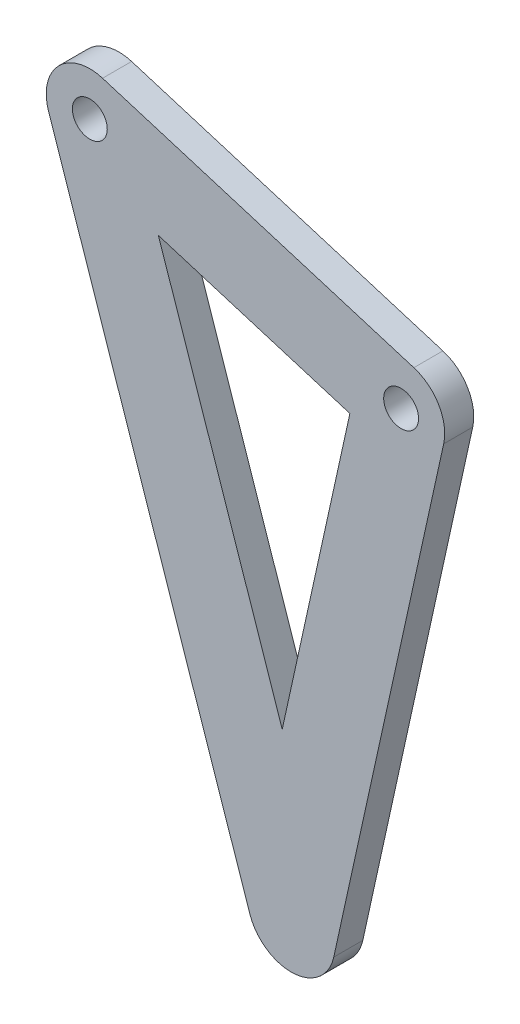
SolidWorks part; units mm, degrees
ref_plane "Plan de face" through (0, 0, 0) normal (0, 0, 1) x (1, 0, 0)
ref_plane "Plan de dessus" through (0, 0, 0) normal (0, 1, 0) x (1, 0, 0)
ref_plane "Plan de droite" through (0, 0, 0) normal (1, 0, 0) x (0, 0, -1)
sketch "Esquisse1" plane through (0, 0, 0) normal (0, 0, 1) x (1, 0, 0)
  line L0 (-104.5852, -42.1267) -> (-51.0249, -58.4761) construction
  line L1 (-102.3955, -34.9534) -> (-48.8353, -51.3029)
  line L2 (-106.7748, -49.2999) -> (-53.2146, -65.6494)
  line L3 (-51.0249, -58.4761) -> (-69.9405, -144.4191) construction
  line L4 (-43.7003, -60.0882) -> (-62.6158, -146.0313)
  line L5 (-58.3496, -56.864) -> (-77.2652, -142.807)
  line L6 (-69.9405, -144.4191) -> (-104.5852, -42.1267) construction
  line L7 (-77.0441, -146.825) -> (-111.6888, -44.5326)
  line L8 (-62.8368, -142.0133) -> (-97.4815, -39.7208)
  line L9 (-92.7916, -53.5684) -> (-71.4762, -116.5046)
  line L10 (-71.4762, -116.5046) -> (-59.8382, -63.6275)
  line L11 (-59.8382, -63.6275) -> (-92.7916, -53.5684)
  line L12 (-43.7003, -60.0882) -> (-62.6158, -146.0313)
  line L13 (-102.3955, -34.9534) -> (-48.8353, -51.3029)
  line L14 (-111.6888, -44.5326) -> (-77.0441, -146.825)
  arc A0 (-102.3955, -34.9534) -> (-106.7748, -49.2999) centre (-104.5852, -42.1267) ccw
  arc A1 (-53.2146, -65.6494) -> (-48.8353, -51.3029) centre (-51.0249, -58.4761) ccw
  arc A2 (-43.7003, -60.0882) -> (-58.3496, -56.864) centre (-51.0249, -58.4761) ccw
  arc A3 (-77.2652, -142.807) -> (-62.6158, -146.0313) centre (-69.9405, -144.4191) ccw
  arc A4 (-77.0441, -146.825) -> (-62.8368, -142.0133) centre (-69.9405, -144.4191) ccw
  arc A5 (-97.4815, -39.7208) -> (-111.6888, -44.5326) centre (-104.5852, -42.1267) ccw
  point P4 (-77.8051, -50.3014)
  point P9 (-60.4827, -101.4476)
  point P18 (-87.2628, -93.2729)
  point P25 (-92.7916, -53.5684)
  point P26 (-71.4762, -116.5046)
  point P27 (-59.8382, -63.6275)
  dimension "D1" = 15
  dimension "D2" = 15
  dimension "D3" = 15
extrude "Boss.-Extru.1" add sketch "Esquisse1" against normal blind 5 contours A5 L8 L2 L5 A2 L1 | A1 A2 L5 L2 | L8 A5 A0 L2 | A3 L5 L8 L2 A0 L7 | A3 A4 L8 L5 | A4 L4 A1 L2 L5 L8
sketch "Esquisse2" plane through (0, 0, 0) normal (0, 0, 1) x (1, 0, 0)
  circle A0 centre (-51.0249, -58.4761) radius 3
  circle A1 centre (-104.5852, -42.1267) radius 3
  dimension "D1" = 6
  dimension "D2" = 6
extrude "Enlèv. mat.-Extru.1" cut sketch "Esquisse2" against normal through all both and the other way through all contours A1 | A0
